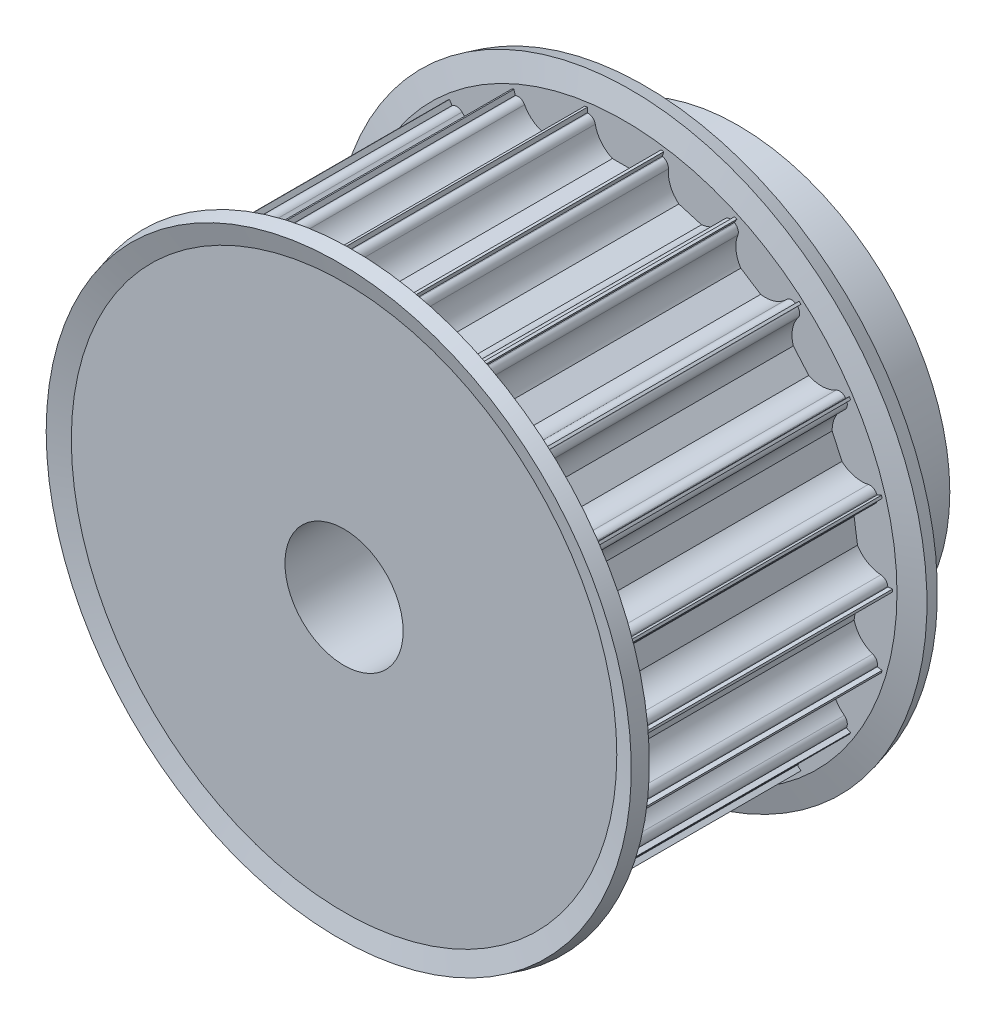
SolidWorks part; units mm, degrees
ref_plane "Front Plane" through (0, 0, 0) normal (0, 0, 1) x (1, 0, 0)
ref_plane "Top Plane" through (0, 0, 0) normal (0, 1, 0) x (1, 0, 0)
ref_plane "Right Plane" through (0, 0, 0) normal (1, 0, 0) x (0, 0, -1)
sketch "Sketch1" plane through (0, 0, 0) normal (1, 0, 0) x (0, 0, -1)
  line L0 (0, 0) -> (27.912, 0) construction
  line L1 (0, 6) -> (40, 6)
  line L2 (40, 6) -> (40, 21.5)
  line L3 (40, 21.5) -> (30, 21.5)
  line L4 (30, 21.5) -> (30, 27.25)
  line L5 (30, 27.25) -> (0, 27.25)
  line L6 (0, 27.25) -> (0, 6)
  dimension "D1" = 27.25
  dimension "D2" = 6
  dimension "D3" = 30
  dimension "D4" = 10
  dimension "D5" = 15.5
revolve "Revolve1" add sketch "Sketch1" angle 360 about L0
sketch "Sketch2" plane through (0, 0, 0) normal (0, 0, 1) x (1, 0, 0)
  line L0 (-3.6742, 26.5) -> (-3.75, 26.5)
  line L1 (-3.75, 26.5) -> (-3.75, 28.5)
  line L2 (-3.75, 28.5) -> (3.75, 28.5)
  line L3 (3.75, 28.5) -> (3.75, 26.5)
  line L4 (3.75, 26.5) -> (3.6742, 26.5)
  line L5 (-1.199, 23.75) -> (1.199, 23.75)
  arc A0 (2.9394, 25.9) -> (1.199, 23.75) centre (0, 26.5) cw
  arc A1 (2.9394, 25.9) -> (3.6742, 26.5) centre (3.6742, 25.75) cw
  arc A2 (-2.9394, 25.9) -> (-3.6742, 26.5) centre (-3.6742, 25.75) ccw
  arc A3 (-1.199, 23.75) -> (-2.9394, 25.9) centre (0, 26.5) cw
  point P8 (0, 28.5)
  point P11 (3, 26.5)
  point P14 (-3, 26.5)
  dimension "D1" = 3
  dimension "D5" = 0.75
  dimension "D2" = 26.5
  dimension "D3" = 7.5
  dimension "D4" = 2
  dimension "D6" = 2.75
extrude "Cut-Extrude1" cut sketch "Sketch2" against normal up to next
pattern_circular "CirPattern1" count 22 over 360 about axis through (0, 0, 0) along (0, 0, 1) of "Cut-Extrude1"
sketch "Sketch3" plane through (0, 0, 0) normal (1, 0, 0) x (0, 0, -1)
  line L0 (15, 26.9539) -> (15, 10.9567) construction
  line L1 (30, 26.9539) -> (0, 26.9539) construction
  line L2 (30, 10.9567) -> (0, 10.9567) construction
  line L4 (30, 27.69) -> (30.5391, 29.7018)
  line L5 (30.5391, 29.7018) -> (29.0902, 30.09)
  line L6 (29.0902, 30.09) -> (28.4471, 27.69)
  line L7 (28.4471, 27.69) -> (28.4471, 21.5)
  line L8 (28.4471, 21.5) -> (30, 21.5)
  line L9 (40, 21.5) -> (30, 21.5) construction
  line L10 (30, 27.69) -> (30, 21.5)
  line L11 (0, 27.69) -> (-0.5391, 29.7018)
  line L12 (-0.5391, 29.7018) -> (0.9098, 30.09)
  line L13 (0.9098, 30.09) -> (1.5529, 27.69)
  line L14 (1.5529, 27.69) -> (1.5529, 21.5)
  line L15 (1.5529, 21.5) -> (0, 21.5)
  line L16 (0, 27.69) -> (0, 21.5)
  line L17 (0, 0) -> (-12.9451, 0) construction
  dimension "D1" = 195
  dimension "D2" = 1.5
  dimension "D3" = 6.19
  dimension "D4" = 2.4
revolve "Revolve2" add sketch "Sketch3" angle 360 about L17
